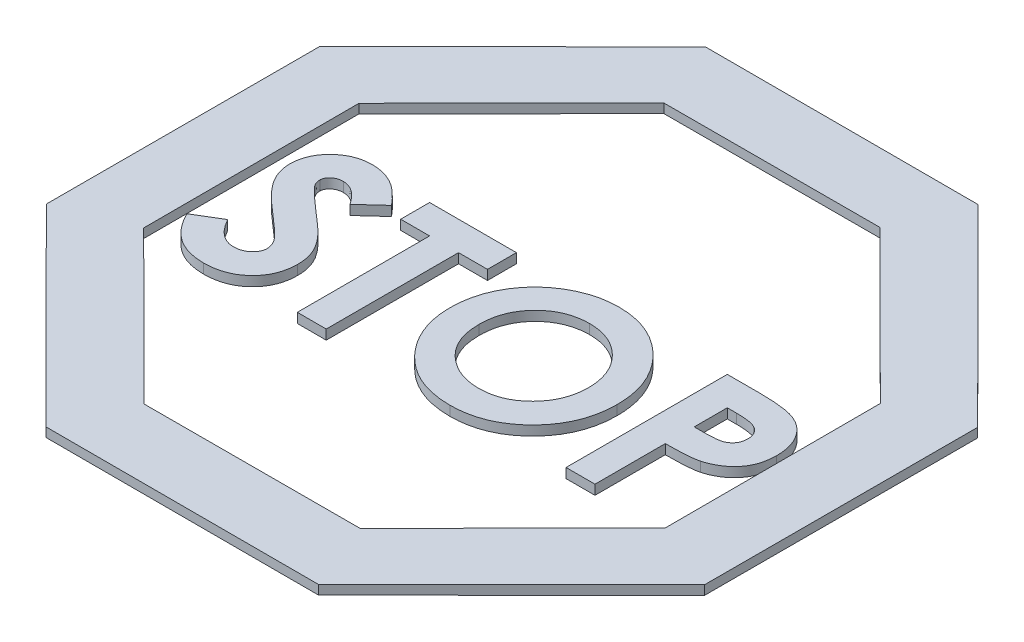
SolidWorks part; units mm, degrees
ref_plane "Front Plane" through (0, 0, 0) normal (0, 0, 1) x (1, 0, 0)
ref_plane "Top Plane" through (0, 0, 0) normal (0, 1, 0) x (1, 0, 0)
ref_plane "Right Plane" through (0, 0, 0) normal (1, 0, 0) x (0, 0, -1)
sketch "Sketch1" plane through (0, 0, 0) normal (0, 1, 0) x (1, 0, 0)
  line L7 (29.5585, -71.5239) -> (71.4761, -29.674)
  line L8 (71.4761, -29.674) -> (71.5239, 29.5585)
  line L9 (71.5239, 29.5585) -> (29.674, 71.4761)
  line L10 (29.674, 71.4761) -> (-29.5585, 71.5239)
  line L11 (-29.5585, 71.5239) -> (-71.4761, 29.674)
  line L12 (-71.4761, 29.674) -> (-71.5239, -29.5585)
  line L13 (-71.5239, -29.5585) -> (-29.674, -71.4761)
  line L14 (-29.674, -71.4761) -> (29.5585, -71.5239)
  line L15 (23.4802, -56.468) -> (56.5319, -23.3259)
  line L16 (56.5319, -23.3259) -> (56.468, 23.4802)
  line L17 (56.468, 23.4802) -> (23.3259, 56.5319)
  line L18 (23.3259, 56.5319) -> (-23.4802, 56.468)
  line L19 (-23.4802, 56.468) -> (-56.5319, 23.3259)
  line L20 (-56.5319, 23.3259) -> (-56.468, -23.4802)
  line L21 (-56.468, -23.4802) -> (-23.3259, -56.5319)
  line L22 (-23.3259, -56.5319) -> (23.4802, -56.468)
  circle A0 centre (0, 0) radius 71.5 construction
  circle A1 centre (0, 0) radius 56.5 construction
  point P0 (0, 0)
  dimension "D1" = 143
  dimension "D2" = 113
extrude "Boss-Extrude2" add sketch "Sketch1" along normal blind 2
sketch "Sketch3" plane through (0, 2, 0) normal (0, 1, 0) x (1, 0, 0)
  line L0 (-56.5319, 23.3259) -> (56.468, 23.4802) construction
  line L1 (56.468, 23.4802) -> (56.5319, -23.3259) construction
  line L2 (56.5319, -23.3259) -> (-56.468, -23.4802) construction
  line L3 (-56.468, -23.4802) -> (-56.5319, 23.3259) construction
  text T0 "STOP" font "Century Gothic" height 35
extrude "Boss-Extrude3" add sketch "Sketch3" along normal blind 0.1 and the other way blind 2 separate body
